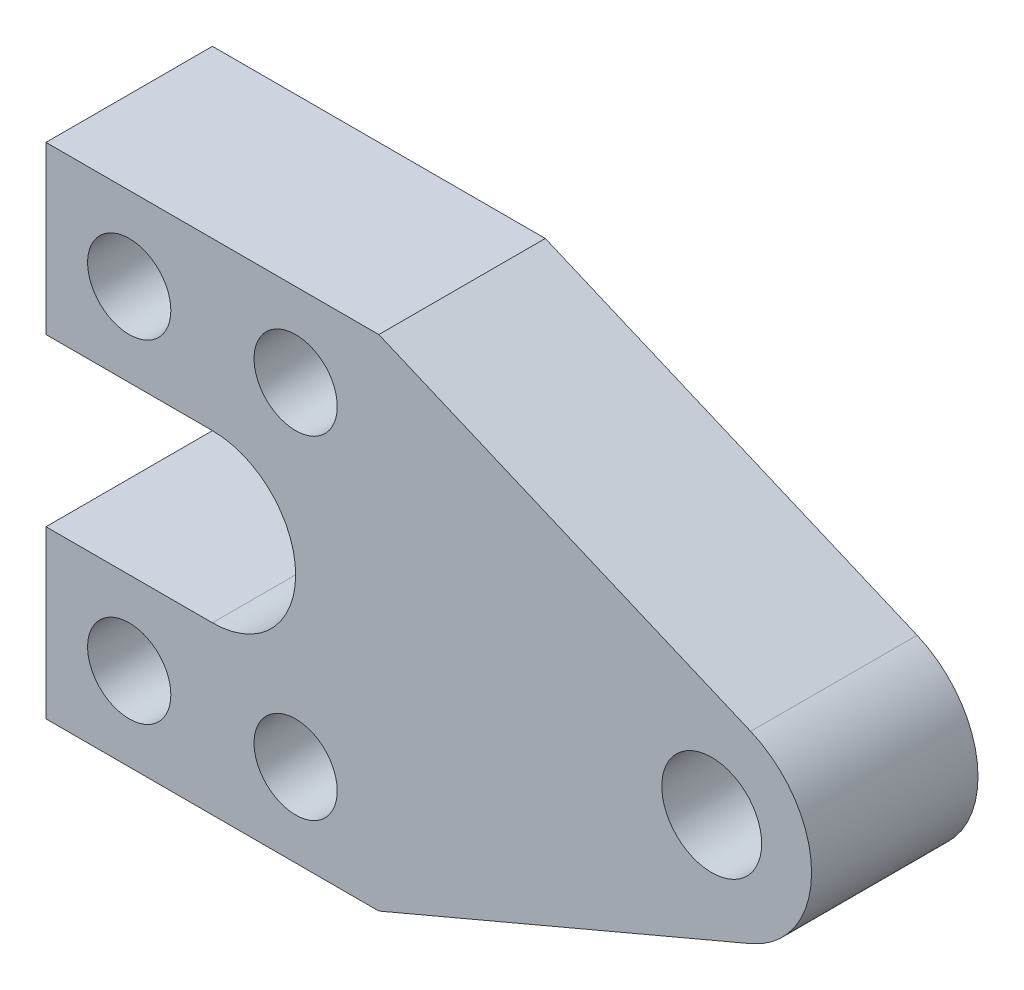
SolidWorks part; units mm, degrees
ref_plane "Front Plane" through (0, 0, 0) normal (0, 0, 1) x (1, 0, 0)
ref_plane "Top Plane" through (0, 0, 0) normal (0, 1, 0) x (1, 0, 0)
ref_plane "Right Plane" through (0, 0, 0) normal (1, 0, 0) x (0, 0, -1)
sketch "Sketch1" plane through (0, 0, 0) normal (0, 0, 1) x (1, 0, 0)
  line L0 (4.9102, 10) -> (10474.0338, 10) construction
  line L1 (10, 5.2395) -> (10, 10474.3631) construction
  line L2 (10, 10) -> (50, 10)
  line L3 (50, 10) -> (94.6856, 28.9526)
  line L4 (94.6856, 51.0474) -> (50, 70)
  line L5 (50, 70) -> (10, 70)
  line L6 (10, 70) -> (10, 50)
  line L7 (10, 50) -> (30, 50)
  line L8 (30, 30) -> (10, 30)
  line L9 (10, 30) -> (10, 10)
  line L10 (10, 40) -> (123.4801, 40) construction
  arc A0 (94.6856, 28.9526) -> (94.6856, 51.0474) centre (90, 40) ccw
  arc A1 (30, 50) -> (30, 30) centre (30, 40) cw
  circle A2 centre (20, 60) radius 5
  circle A3 centre (40, 60) radius 5
  circle A4 centre (20, 20) radius 5
  circle A5 centre (40, 20) radius 5
  circle A6 centre (90, 40) radius 6
  dimension "D4" = 12
  dimension "D7" = 10
  dimension "D12" = 10
  dimension "D14" = 12
  dimension "D1" = 10
  dimension "D2" = 10
  dimension "D3" = 60
  dimension "D5" = 80
  dimension "D6" = 20
  dimension "D8" = 40
  dimension "D9" = 20
  dimension "D10" = 10
  dimension "D11" = 40
  dimension "D13" = 30
extrude "Boss-Extrude1" add sketch "Sketch1" along normal blind 20
